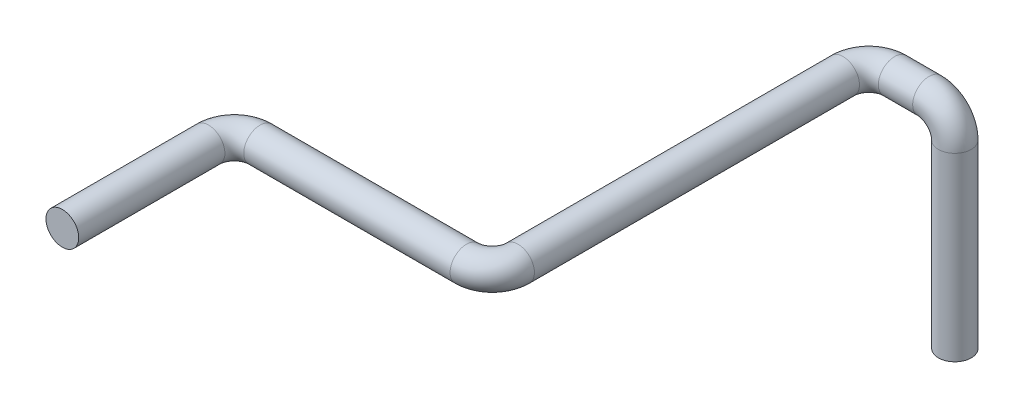
SolidWorks part; units mm, degrees
ref_plane "Alzado" through (0, 0, 0) normal (0, 0, 1) x (1, 0, 0)
ref_plane "Planta" through (0, 0, 0) normal (0, 1, 0) x (1, 0, 0)
ref_plane "Vista lateral" through (0, 0, 0) normal (1, 0, 0) x (0, 0, -1)
sketch "Croquis1" plane through (0, 0, 0) normal (0, 1, 0) x (1, 0, 0)
  circle A0 centre (0, 0) radius 9.525
  dimension "D1" = 19.05
extrude "Saliente-Extruir1" add sketch "Croquis1" along normal blind 10
sketch3d "Croquis3D1"
  line L0 (0, 10, 0) -> (0, 105, 0)
  line L1 (0, 10, 0) -> (0, 0, 0) construction
  line L2 (-15, 120, 0) -> (-35, 120, 0)
  line L3 (-50, 120, 15) -> (-50, 120, 204)
  line L4 (-65, 120, 219) -> (-185, 120, 219)
  line L5 (-200, 120, 234) -> (-200, 120, 319)
  arc A0 (-50, 120, 204) -> (-65, 120, 219) centre (-65, 120, 204) ccw
  arc A1 (-35, 120, 0) -> (-50, 120, 15) centre (-35, 120, 15) ccw
  arc A2 (0, 105, 0) -> (-15, 120, 0) centre (-15, 105, 0) ccw
  arc A3 (-185, 120, 219) -> (-200, 120, 234) centre (-185, 120, 234) ccw
  point P9 (-50, 120, 219)
  point P10 (-65, 105, 204)
  point P13 (-50, 120, 0)
  point P14 (-35, 135, 15)
  point P17 (0, 120, 0)
  point P18 (-15, 105, 15)
  point P22 (-200, 120, 219)
  point P23 (-185, 135, 234)
  dimension "D5" = 15
  dimension "D7" = 15
  dimension "D1" = 110
  dimension "D2" = 50
  dimension "D3" = 219
  dimension "D4" = 150
  dimension "D6" = 100
sketch "Croquis2" plane through (0, 10, 0) normal (0, 1, 0) x (1, 0, 0)
  circle A0 centre (0, 0) radius 9.525
sweep "Barrer1" add profiles "Croquis2" path "Croquis3D1"
